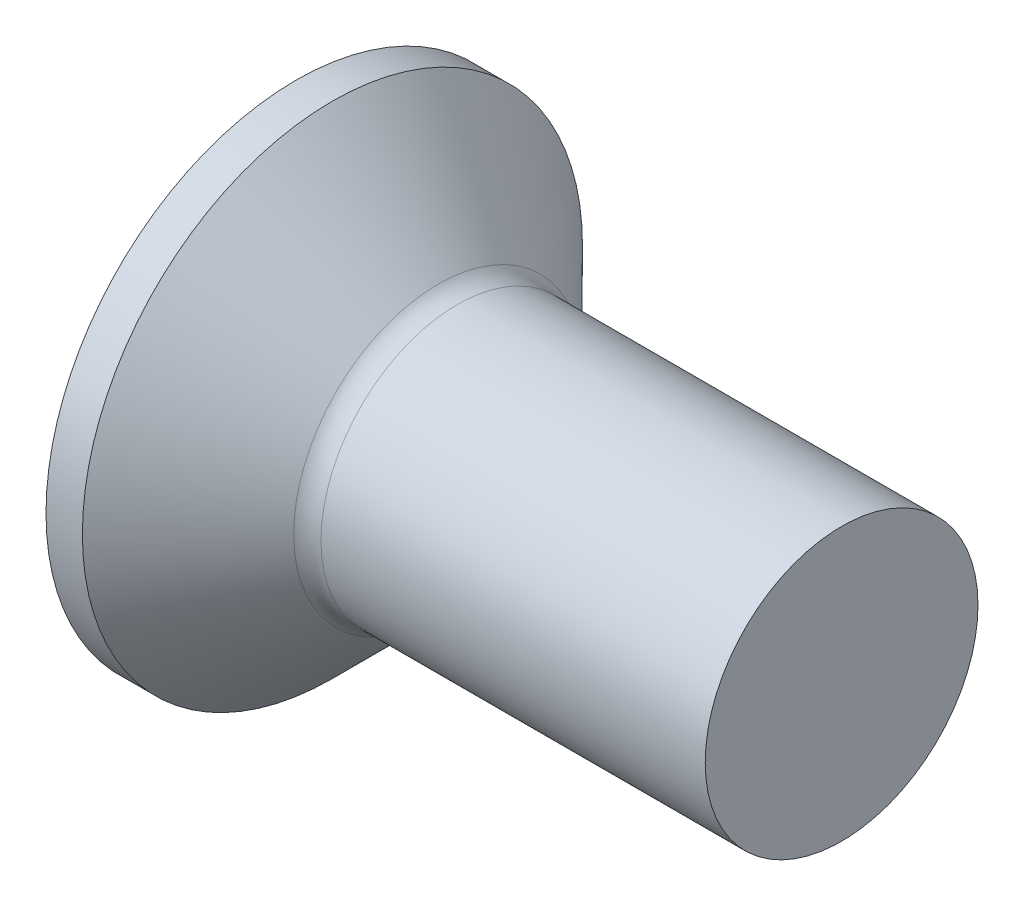
SolidWorks part; units mm, degrees
material "Alloy Steel"
ref_plane "Front Plane" through (0, 0, 0) normal (0, 0, 1) x (1, 0, 0)
ref_plane "Top Plane" through (0, 0, 0) normal (0, 1, 0) x (1, 0, 0)
ref_plane "Right Plane" through (0, 0, 0) normal (1, 0, 0) x (0, 0, -1)
sketch "BodySke" plane through (0, 0, 0) normal (0, 0, 1) x (1, 0, 0)
  line L0 (0, 0) -> (111.3824, 0) construction
  line L1 (0, 0) -> (0, 2.75)
  line L2 (0, 2.75) -> (0.4, 2.75)
  line L3 (0.4, 2.75) -> (1.65, 1.5)
  line L4 (1.65, 1.5) -> (6, 1.5)
  line L5 (6, 1.5) -> (6, 0)
  line L6 (2.1187, 5.324) -> (2.1188, -9.3939) construction
  line L7 (0, 0) -> (6, 0)
  line L8 (2.4, 8.824) -> (2.4, -4.958) construction
  line L9 (0, -2.75) -> (0.4, -2.75) construction
  line L10 (0.4, -2.75) -> (1.65, -1.5) construction
  line L11 (1.65, -1.5) -> (6, -1.5) construction
  point P10 (6, 1.2919)
  dimension "Thread_minor" = 2.5838
  dimension "Diameter" = 3
  dimension "Thread_length" = 3.6
  dimension "Length" = 6
  dimension "Head_ang" = 90
  dimension "Head_height" = 1.65
  dimension "Head_dia" = 5.5
  dimension "Advance" = 0.4688
revolve "BaseBody" add sketch "BodySke" angle 360 about L0
cosmetic thread "ThreadCosmetic" [suppressed] parameters "Thread_minor"=2.5838
fillet "Fillet1" radius 0.3 1 edges at (1.65, 0, 1.5)
ref_plane "Plane1" through (1.86, 0, 0) normal (1, 0, 0) x (0, 0, -1)
sketch "RecSkeTop" plane through (0, 0, 0) normal (-1, 0, 0) x (0, 0, 1)
  line L1 (-0.3465, 1.575) -> (0.3465, 1.575)
  line L2 (-0.3465, 1.575) -> (-0.3465, -1.575)
  line L3 (-0.3465, -1.575) -> (0.3465, -1.575)
  line L4 (0.3465, 1.575) -> (0.3465, -1.575)
  dimension "Cross_dia" = 3.15
  dimension "D1" = 1.575
  dimension "D2" = 0.693
  dimension "D3" = 0.3465
sketch "RecSkeBot" plane through (1.86, 0, 0) normal (1, 0, 0) x (0, 0, -1)
  line L0 (0.3465, 1.575) -> (0.3465, -1.575) construction
  line L1 (0.3465, 0.6476) -> (-0.3465, 0.6476)
  line L2 (0.3465, 0.6476) -> (0.3465, -0.6476)
  line L3 (0.3465, -0.6476) -> (-0.3465, -0.6476)
  line L4 (-0.3465, 0.6476) -> (-0.3465, -0.6476)
  line L5 (-0.3465, 1.575) -> (-0.3465, -1.575) construction
  dimension "D1" = 1.2953
  dimension "D2" = 0.6476
loft "Recess" cut profiles "RecSkeTop", "RecSkeBot"
pattern_circular "RecPat" count 2 every 90 about axis through (0, 0, 0) along (1, 0, 0) of "Recess"
sketch "RecCorSke" plane through (0, 0, 0) normal (0, 0, 1) x (1, 0, 0)
  line L0 (0, 0) -> (57.5987, 0) construction
  line L1 (0, 0) -> (0, 0.7623)
  line L2 (0, 2.75) -> (0, -2.75) construction
  line L3 (0, 0.7623) -> (1.86, 0.6322)
  line L4 (1.86, 0.6322) -> (2.0654, 0)
  line L5 (2.0654, 0) -> (0, 0)
  dimension "D1" = 18
  dimension "D2" = 1.86
  dimension "D3" = 0.7623
  dimension "D4" = 4
revolve "RecessCore" cut sketch "RecCorSke" angle 360 about L0
sketch "ThdSchSke" plane through (0, 0, 0) normal (0, 0, 1) x (1, 0, 0)
  line L0 (0, 0) -> (55.1256, 0) construction
  line L1 (0, 0) -> (111.3824, 0) construction
  line L2 (5.8798, 1.5) -> (5.8798, 1.7403)
  line L3 (5.8798, 1.7403) -> (6.1202, 1.7403)
  line L4 (6.1202, 1.7403) -> (6.1202, 1.5)
  line L5 (6.1202, 1.5) -> (6, 1.2919)
  line L6 (6, 1.2919) -> (5.8798, 1.5)
  line L7 (1.65, 1.5) -> (6, 1.5) construction
  line L13 (6, 1.5) -> (6, 0) construction
revolve "ThreadSchematic" [suppressed] cut sketch "ThdSchSke" angle 360 about L0
pattern_linear "ThdSchPat" [suppressed] count 7 along (1, 0, 0)
equation "\"Thread_minor@ThreadCosmetic\" = \"Thread_minor@BodySke\""
equation "\"D1@RecSkeTop\" = \"Cross_dia@RecSkeTop\" / 2"
equation "\"D2@RecSkeTop\" = \"Cross_dia@RecSkeTop\" * 0.22"
equation "\"D3@RecSkeTop\" = \"D2@RecSkeTop\" / 2"
equation "\"D1@RecSkeBot\" = \"Cross_dia@RecSkeTop\" - 2 * \"Cross_depth@Plane1\" *  tan( 26.5 * 0.017453292 ) "
equation "\"D2@RecSkeBot\" = \"D1@RecSkeBot\" / 2"
equation "\"D2@RecCorSke\" = \"Cross_depth@Plane1\""
equation "\"D3@RecCorSke\" = \"D2@RecSkeTop\" * 1.1"
equation "\"Advance@ThdSchPat\" = \"Advance@BodySke\""
equation "\"D1@ThdSchPat\" =  int( \"Thread_length@BodySke\" / \"Advance@ThdSchPat\" ) "
equation "\"Mass\"= \"SW-질량\" / 1000"
equation "\"Thread_minor@BodySke\"= \"Diameter@BodySke\" * ( 6.89 / 8 )"
equation "\"Thread_length@BodySke\"= \"Length@BodySke\" * ( 30 / 50 )"
equation "\"Radius@Fillet1\"= \"Diameter@BodySke\" * 0.1"
equation "\"Cross_depth@Plane1\"= \"Diameter@BodySke\" * ( 4.96 / 8 )"
equation "\"Cross_dia@RecSkeTop\"= \"Diameter@BodySke\" * ( 8.4 / 8 )"
equation "\"Advance@BodySke\"= \"Diameter@BodySke\" * ( 1.25 / 8 )"
